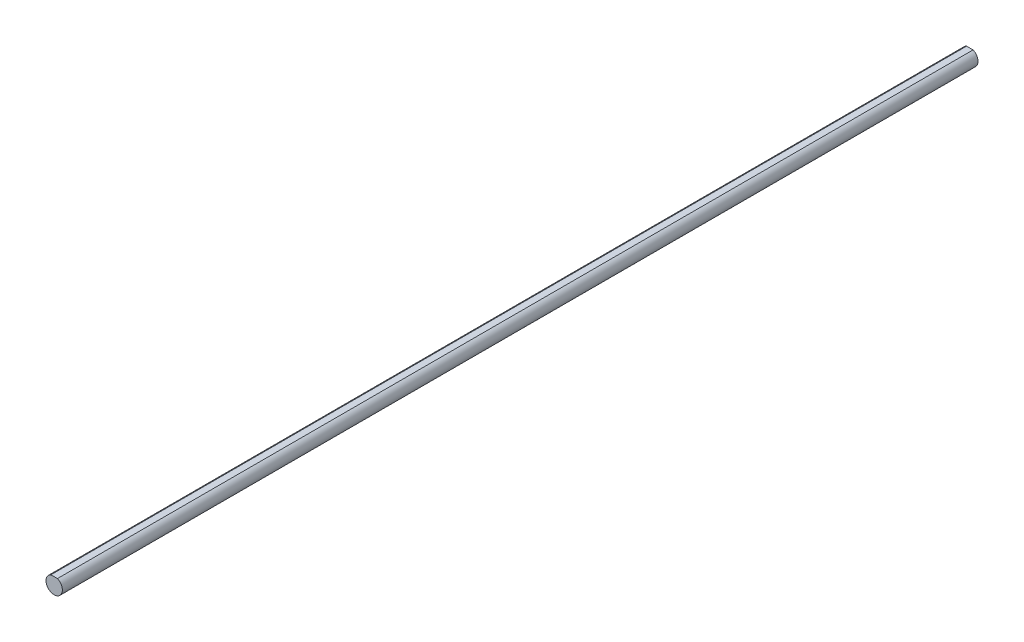
SolidWorks part; units mm, degrees
ref_plane "Plan de face" through (0, 0, 0) normal (0, 0, 1) x (1, 0, 0)
ref_plane "Plan de dessus" through (0, 0, 0) normal (0, 1, 0) x (1, 0, 0)
ref_plane "Plan de droite" through (0, 0, 0) normal (1, 0, 0) x (0, 0, -1)
sketch "Esquisse1" plane through (0, 0, 0) normal (0, 0, 1) x (1, 0, 0)
  line L0 (-1, 2.2913) -> (1, 2.2913)
  circle A0 centre (0, 0) radius 2.5
  dimension "D1" = 5
  dimension "D2" = 2
extrude "Boss.-Extru.1" add sketch "Esquisse1" along normal blind 280 contours L0 A0
